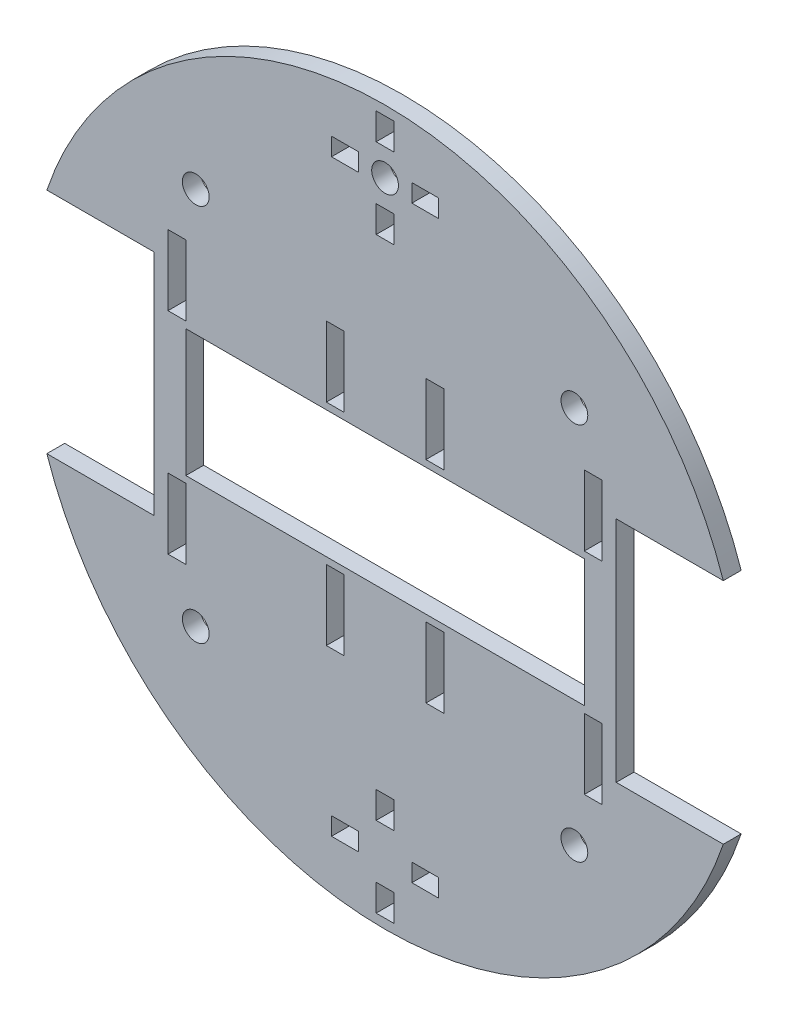
SolidWorks part; units mm, degrees
ref_plane "Front Plane" through (0, 0, 0) normal (0, 0, 1) x (1, 0, 0)
ref_plane "Top Plane" through (0, 0, 0) normal (0, 1, 0) x (1, 0, 0)
ref_plane "Right Plane" through (0, 0, 0) normal (1, 0, 0) x (0, 0, -1)
sketch "Sketch1" plane through (0, 0, 0) normal (0, 0, 1) x (1, 0, 0)
  line L0 (0, 127) -> (0, -127) construction
  line L1 (-127, 0) -> (127, 0) construction
  line L2 (120.3355, -40.6) -> (82.2355, -40.6)
  line L3 (-120.3355, -40.6) -> (-82.2355, -40.6)
  line L5 (-120.3355, 40.6) -> (-82.2355, 40.6)
  line L6 (-82.2355, -40.6) -> (-82.2355, 40.6)
  line L7 (-133.6692, -30.6334) -> (-82.2355, 40.6) construction
  line L8 (-133.6692, 30.6334) -> (-82.2355, -40.6) construction
  line L9 (82.2355, -40.6) -> (82.2355, 40.6)
  line L10 (120.3355, 40.6) -> (82.2355, 40.6)
  arc A0 (-120.3355, -40.6) -> (120.3355, -40.6) centre (0, 0) ccw
  arc A1 (120.3355, 40.6) -> (-120.3355, 40.6) centre (0, 0) ccw
  point P7 (-111.5505, 0)
  dimension "D1" = 254
  dimension "D2" = 38.1
  dimension "D3" = 81.2
  dimension "D4" = 40.6
extrude "Boss-Extrude1" add sketch "Sketch1" along normal blind 6.35
sketch "Sketch2" plane through (0, 0, 6.35) normal (0, 0, 1) x (1, 0, 0)
  line L0 (0, 127) -> (0, -127) construction
  line L1 (-127, 0) -> (127, 0) construction
  line L2 (20.8855, 50) -> (14.5355, 50)
  line L3 (-77.2355, 25) -> (-70.8855, 25)
  line L4 (-77.2355, 25) -> (-77.2355, 50)
  line L5 (-77.2355, 50) -> (-70.8855, 50)
  line L6 (-70.8855, 25) -> (-70.8855, 50)
  line L7 (-20.8855, 25) -> (-14.5355, 25)
  line L8 (-20.8855, 25) -> (-20.8855, 50)
  line L9 (-20.8855, 50) -> (-14.5355, 50)
  line L10 (-14.5355, 25) -> (-14.5355, 50)
  line L11 (14.5355, 25) -> (14.5355, 50)
  line L12 (20.8855, 25) -> (14.5355, 25)
  line L13 (20.8855, 25) -> (20.8855, 50)
  line L14 (77.2355, 50) -> (70.8855, 50)
  line L15 (70.8855, 25) -> (70.8855, 50)
  line L16 (77.2355, 25) -> (70.8855, 25)
  line L17 (77.2355, 25) -> (77.2355, 50)
  line L18 (77.2355, -25) -> (77.2355, -50)
  line L19 (77.2355, -25) -> (70.8855, -25)
  line L20 (70.8855, -25) -> (70.8855, -50)
  line L21 (77.2355, -50) -> (70.8855, -50)
  line L22 (20.8855, -25) -> (20.8855, -50)
  line L23 (20.8855, -25) -> (14.5355, -25)
  line L24 (14.5355, -25) -> (14.5355, -50)
  line L25 (20.8855, -50) -> (14.5355, -50)
  line L26 (-20.8855, -50) -> (-14.5355, -50)
  line L27 (-14.5355, -25) -> (-14.5355, -50)
  line L28 (-20.8855, -25) -> (-14.5355, -25)
  line L29 (-20.8855, -25) -> (-20.8855, -50)
  line L30 (-77.2355, -50) -> (-70.8855, -50)
  line L31 (-70.8855, -25) -> (-70.8855, -50)
  line L32 (-77.2355, -25) -> (-70.8855, -25)
  line L33 (-77.2355, -25) -> (-77.2355, -50)
  line L35 (-82.2355, 40.6) -> (-82.2355, -40.6) construction
  circle A0 centre (0, 0) radius 127 construction
  dimension "D1" = 6.35
  dimension "D2" = 6.35
  dimension "D3" = 50
  dimension "D4" = 25
  dimension "D5" = 25
  dimension "D6" = 25
  dimension "D7" = 25
  dimension "D8" = 5
extrude "Cut-Extrude1" cut sketch "Sketch2" against normal through all both and the other way through all
sketch "Sketch5" plane through (0, 0, 6.35) normal (0, 0, 1) x (1, 0, 0)
  line L0 (0, 127) -> (0, -127) construction
  line L1 (134.3805, 0) -> (-129.0635, 0) construction
  line L2 (-82.2355, 40.6) -> (-82.2355, -40.6) construction
  line L7 (-70.8855, -22.625) -> (70.8855, -22.625)
  line L8 (-70.8855, -22.625) -> (-70.8855, 22.625)
  line L9 (-70.8855, 22.625) -> (70.8855, 22.625)
  line L10 (70.8855, -22.625) -> (70.8855, 22.625)
  line L11 (-70.8855, -22.625) -> (70.8855, 22.625) construction
  line L12 (-70.8855, 22.625) -> (70.8855, -22.625) construction
  arc A0 (120.3355, 40.6) -> (-120.3355, 40.6) centre (0, 0) ccw construction
  arc A1 (-120.3355, -40.6) -> (120.3355, -40.6) centre (0, 0) ccw construction
  point P12 (0, 0)
  dimension "D2" = 45.25
  dimension "D1" = 11.35
extrude "Cut-Extrude2" cut sketch "Sketch5" against normal through all both and the other way through all
sketch "Sketch6" plane through (0, 0, 6.35) normal (0, 0, 1) x (1, 0, 0)
  line L0 (0, 0) -> (-120.8378, 120.8378) construction
  line L1 (0, 0) -> (107.9366, 107.9366) construction
  line L2 (0, 0) -> (-95.6995, -95.6995) construction
  line L3 (0, 0) -> (97.5241, -97.5241) construction
  line L4 (0, 148.004) -> (0, -151.8468) construction
  line L5 (0, 0) -> (122.2309, 0) construction
  line L6 (0, 0) -> (-149.9343, 0) construction
  line L7 (-149.9343, 0) -> (122.2309, 0) construction
  circle A0 centre (-67.3519, 67.3519) radius 4.7625
  circle A1 centre (67.3519, 67.3519) radius 4.7625
  circle A2 centre (67.3519, -67.3519) radius 4.7625
  circle A3 centre (-67.3519, -67.3519) radius 4.7625
  dimension "D1" = 9.525
  dimension "D2" = 95.25
extrude "Cut-Extrude3" cut sketch "Sketch6" against normal through all both and the other way through all
sketch "Sketch7" plane through (0, 0, 6.35) normal (0, 0, 1) x (1, 0, 0)
  line L0 (0, 151.9569) -> (0, -146.0017) construction
  line L2 (-139.2386, 0) -> (138.171, 0) construction
  circle A2 centre (0, 104.5375) radius 4.7625
  dimension "D1" = 9.525
  dimension "D2" = 104.5375
extrude "Cut-Extrude4" cut sketch "Sketch7" against normal through all both and the other way through all
sketch "Sketch8" plane through (0, 0, 6.35) normal (0, 0, 1) x (1, 0, 0)
  line L0 (0, 127) -> (0, -127) construction
  line L1 (-139.7296, 0) -> (135.1505, 0) construction
  line L28 (0, 127) -> (0, 109.3) construction
  line L29 (-4.7625, 104.5375) -> (4.7625, 104.5375) construction
  line L30 (-3.175, 114.0625) -> (3.175, 114.0625)
  line L31 (-3.175, 114.0625) -> (-3.175, 123.5875)
  line L32 (-3.175, 123.5875) -> (3.175, 123.5875)
  line L33 (3.175, 114.0625) -> (3.175, 123.5875)
  line L34 (-3.175, 114.0625) -> (3.175, 123.5875) construction
  line L35 (-3.175, 123.5875) -> (3.175, 114.0625) construction
  line L36 (-3.175, 85.4875) -> (3.175, 85.4875)
  line L37 (3.175, 95.0125) -> (3.175, 85.4875)
  line L38 (-3.175, 95.0125) -> (3.175, 95.0125)
  line L39 (-3.175, 95.0125) -> (-3.175, 85.4875)
  line L40 (-3.175, -95.0125) -> (-3.175, -85.4875)
  line L41 (-3.175, -95.0125) -> (3.175, -95.0125)
  line L42 (3.175, -95.0125) -> (3.175, -85.4875)
  line L43 (-3.175, -85.4875) -> (3.175, -85.4875)
  line L44 (-3.175, -123.5875) -> (3.175, -123.5875)
  line L45 (3.175, -114.0625) -> (3.175, -123.5875)
  line L46 (-3.175, -114.0625) -> (3.175, -114.0625)
  line L47 (-3.175, -114.0625) -> (-3.175, -123.5875)
  line L48 (-9.525, 107.8587) -> (-19.05, 107.8587)
  line L49 (9.525, 101.5087) -> (19.05, 101.5087)
  line L50 (9.525, 101.5087) -> (9.525, 107.8587)
  line L51 (9.525, 107.8587) -> (19.05, 107.8587)
  line L52 (19.05, 101.5087) -> (19.05, 107.8587)
  line L53 (9.525, 101.5087) -> (19.05, 107.8587) construction
  line L54 (9.525, 107.8587) -> (19.05, 101.5087) construction
  line L55 (-19.05, 101.5087) -> (-19.05, 107.8587)
  line L56 (-9.525, 101.5087) -> (-19.05, 101.5087)
  line L57 (-9.525, 101.5087) -> (-9.525, 107.8587)
  line L58 (9.525, -107.8587) -> (19.05, -107.8587)
  line L59 (19.05, -101.5087) -> (19.05, -107.8587)
  line L60 (9.525, -101.5087) -> (19.05, -101.5087)
  line L61 (9.525, -101.5087) -> (9.525, -107.8587)
  line L62 (-9.525, -101.5087) -> (-9.525, -107.8587)
  line L63 (-9.525, -101.5087) -> (-19.05, -101.5087)
  line L64 (-19.05, -101.5087) -> (-19.05, -107.8587)
  line L65 (-9.525, -107.8587) -> (-19.05, -107.8587)
  arc A0 (120.3355, 40.6) -> (-120.3355, 40.6) centre (0, 0) ccw construction
  arc A1 (-120.3355, -40.6) -> (120.3355, -40.6) centre (0, 0) ccw construction
  circle A2 centre (0, 104.5375) radius 4.7625 construction
  point P16 (0, 121.4008)
  point P17 (0, 118.825)
  point P34 (14.2875, 104.6837)
  dimension "D1" = 6.35
  dimension "D3" = 9.525
  dimension "D4" = 6.35
  dimension "D5" = 9.525
  dimension "D6" = 9.525
  dimension "D2" = 9.525
extrude "Cut-Extrude5" cut sketch "Sketch8" against normal through all both and the other way through all
equation "\"Wheel Thickness\"= 1in"
equation "\"Wheel Diameter\"= 3in"
equation "\"Motor Rear Diameter\" = 36.2mm"
equation "\"Motor Front Diameter\" = 12mm"
equation "\"Material Thickness\" = .25in"
equation "\"Wheel Cutout Diameter\"= 2cm"
equation "\"Motor Mount Tab Thickness\" = 100mm"
equation "\"Motor Mount Tab Height\" = 40mm"
equation "\"Motor Shaft Diameter\" = 3mm"
equation "\"Base Diameter\" = 10in"
equation "\"D1@Sketch1\"=\"Base Diameter\""
equation "\"D1@Boss-Extrude1\"=\"Material Thickness\""
equation "\"D1@Sketch2\"=\"Material Thickness\""
equation "\"D2@Sketch2\"=\"Material Thickness\""
equation "\"D4@Sketch2\"=\"Motor Mount Tab Thickness\"/4"
equation "\"D5@Sketch2\"=\"Motor Mount Tab Thickness\"/4"
equation "\"D6@Sketch2\"=\"Motor Mount Tab Thickness\"/4"
equation "\"D7@Sketch2\"=\"Motor Mount Tab Thickness\"/4"
equation "\"Wheel Radius Clearance\" = 5mm"
equation "\"Wheel Cutout Width\" = 1.5in"
equation "\"D2@Sketch1\"=\"Wheel Cutout Width\""
equation "\"D3@Sketch1\"=\"Wheel Diameter\"+\"Wheel Radius Clearance\""
equation "\"D4@Sketch1\"=(\"Wheel Diameter\"+\"Wheel Radius Clearance\")/2"
equation "\"Wheel Mount Distance\" = 5mm"
equation "\"D8@Sketch2\"=\"Wheel Mount Distance\""
equation "\"Motor Mount Distance\" = 50mm"
equation "\"D3@Sketch2\"=\"Motor Mount Distance\""
equation "\"Motor Cutout Length\" = 6in"
equation "\"D2@Sketch5\"=1.25*\"Motor Rear Diameter\""
equation "\"D1@Sketch5\"=\"Wheel Mount Distance\"+\"Material Thickness\""
equation "\"Rod Diameter\" = 3/8in"
equation "\"D1@Sketch6\"=\"Rod Diameter\""
equation "\"D2@Sketch6\"=(\"Base Diameter\"/2)*.75"
equation "\"D1@Sketch7\"=\"Rod Diameter\""
equation "\"D2@Sketch7\"=((\"Base Diameter\"/2)-5mm)-((\"Rod Diameter\"/2)+.5)"
equation "\"Motor Cutout Height\" = 2in "
equation "\"Rod Length\" = 1.5in"
equation "\"Barrel Front Length\" = 1.8in"
equation "\"Barrerl Rear Length\" = 5in "
equation "\"Barrel Fillet Radius\" = 1in "
equation "\"Barrel Angle\" = 20deg"
equation "\"Barrel Diameter\" = 50mm"
equation "\"Barrel Shell Width\" = 2mm"
equation "\"Second Level Diameter\" = 10in"
equation "\"Ball Diameter\" = 40mm"
equation "\"Third Level Length\" = 9in"
equation "\"Third Level Height\" = 9in"
equation "\"Barrel Tab Clearance\" = 5mm"
equation "\"Barrel Tab Distance Away\" = 2mm"
equation "\"Hole Distance Apart\" = 2.8in"
equation "\"Barrel Tab Distance\"= 1.5in "
equation "\"Third Level Rod Distance\" = .5in"
equation " \"Second Rod Diameter\" = 3/8in"
equation "\"Second Rod Length\" = 3.88in"
equation "\"Bumper Wheel Clearance\" = 1.2in"
equation "\"Servo Tab Height\" = 4in"
equation "\"Servo Tab Width\" = 2in"
equation "\"Servo Tab Hole Horizontal Distance\" = 1in"
equation "\"Servo Tab Hole Vertical Distance\" = 1.5in "
equation "\"Servo Hole Vertical Distance\" = 3in"
equation "\"Servo Hole Diameter\" = 1/4in"
equation "\"Servo Hole Shaft Length\" = 1.45in"
equation "\"Third Rod Length\" = 3.83in"
equation "\"Third Rod Diameter\" = 3/8in"
equation "\"Third Rod Radius Distance\" = 1.5in"
equation "\"Third Rod Angle Distance\" = 20deg"
equation "\"Fourth Level Diameter\" = 3.5in"
equation "\"Skid Length\" = 2in"
equation "\"Skid Width\" = 1.5in"
equation "\"Skid Clearance\" = 3mm"
equation "\"D1@Sketch8\"=\"Material Thickness\""
equation "\"D3@Sketch8\"=\"Skid Width\"/4"
equation "\"D4@Sketch8\"=\"Material Thickness\""
equation "\"D5@Sketch8\"=\"Skid Width\"/4"
equation "\"D6@Sketch8\"=\"Skid Width\"/4"
equation "\"D2@Sketch8\"=\"Skid Width\"/4"
